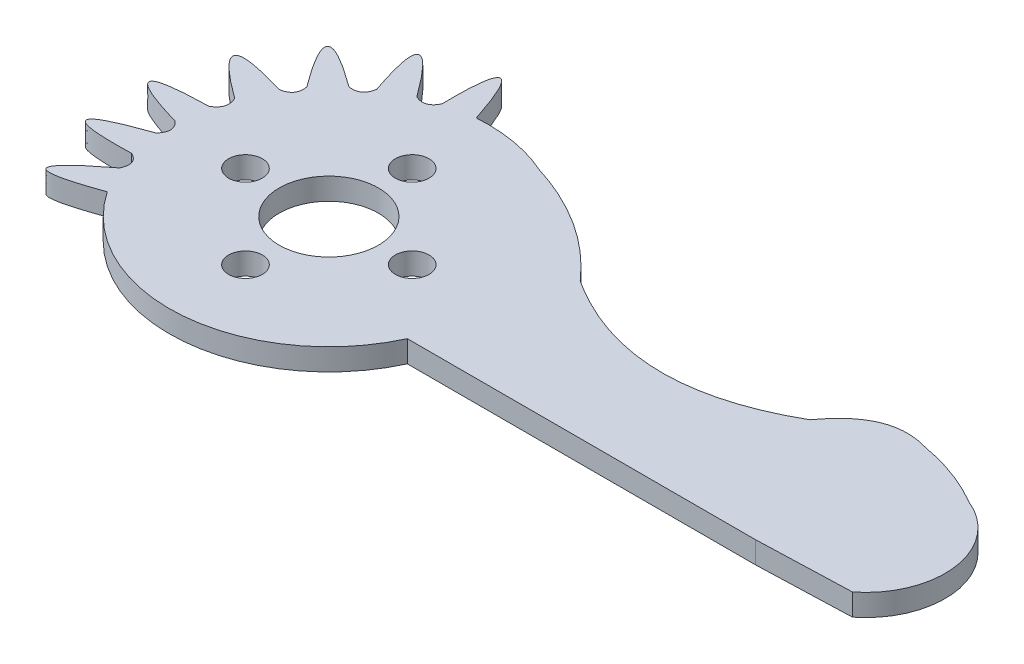
SolidWorks part; units mm, degrees
ref_plane "前视基准面" through (0, 0, 0) normal (0, 0, 1) x (1, 0, 0)
ref_plane "上视基准面" through (0, 0, 0) normal (0, 1, 0) x (1, 0, 0)
ref_plane "右视基准面" through (0, 0, 0) normal (1, 0, 0) x (0, 0, -1)
sketch "草图1" plane through (0, 0, 0) normal (0, 1, 0) x (1, 0, 0)
  line L0 (14.611, -6.7) -> (49.6904, -6.7)
  line L2 (49.6904, -6.7) -> (59.1421, -6.3765)
  arc A0 (6.5551, 14.6766) -> (-1.174, 16.031) centre (0, 0) ccw
  arc A1 (59.1421, -6.3765) -> (57.1955, 7.3271) centre (54.1955, -0.0891) ccw
  arc A4 (-13.3181, -9) -> (14.611, -6.7) centre (0, 0) ccw
  circle A10 centre (0, 0) radius 5
  circle A11 centre (0, 8.4) radius 1.7
  circle A12 centre (8.4, 0) radius 1.7
  circle A13 centre (-8.4, 0) radius 1.7
  circle A14 centre (0, -8.4) radius 1.7
  spline S0 degree 3 poles (50.3471, 9.8802) (52.7614, 9.4439) (55.0442, 8.5928) (57.1955, 7.3271) knots 0.288437 0.288437 0.288437 0.288437 1 1 1 1
  spline S1 degree 2 poles (-14.7879, -6.3) (-14.1793, -5.0235) (-15.4558, -4.4148) knots 0 0 0 1 1 1
  spline S2 degree 2 poles (-13.3181, -9) (-22.836, -12.4311) (-14.7879, -6.3) knots 0 0 0 1 1 1
  spline S3 degree 2 poles (6.5551, 14.6766) (13.509, 12.4928) (18.294, 7.0371) knots 0 0 0 1 1 1
  spline S4 degree 2 poles (-15.4558, -4.4148) (-25.5664, -4.7364) (-16.0116, -1.4148) knots 0 0 0 1 1 1
  spline S5 degree 2 poles (-16.0116, -1.4148) (-15.0379, -0.3941) (-16.0633, 0.5852) knots 0 0 0 1 1 1
  spline S6 degree 2 poles (-16.0633, 0.5852) (-25.7809, 3.3882) (-15.669, 3.5852) knots 0 0 0 1 1 1
  spline S7 degree 2 poles (-15.669, 3.5852) (-14.4125, 4.2993) (-15.0724, 5.5852) knots 0 0 0 1 1 1
  spline S8 degree 2 poles (-15.0724, 5.5852) (-23.2951, 11.5171) (-13.5892, 8.5852) knots 0 0 0 1 1 1
  spline S9 degree 2 poles (-13.5892, 8.5852) (-12.193, 8.8101) (-12.4179, 10.2063) knots 0 0 0 1 1 1
  spline S10 degree 2 poles (-12.4179, 10.2063) (-18.4607, 18.314) (-10.305, 12.3361) knots 0 0 0 1 1 1
  spline S11 degree 2 poles (-10.305, 12.3361) (-8.9071, 12.1223) (-8.6933, 13.5203) knots 0 0 0 1 1 1
  spline S12 degree 2 poles (-8.6933, 13.5203) (-11.9612, 23.0896) (-6.0295, 14.9002) knots 0 0 0 1 1 1
  spline S13 degree 2 poles (-6.0295, 14.9002) (-4.7643, 14.2684) (-4.1325, 15.5337) knots 0 0 0 1 1 1
  spline S14 degree 2 poles (-4.1325, 15.5337) (-4.3112, 25.644) (-1.174, 16.031) knots 0 0 0 1 1 1
  spline S15 degree 3 poles (41.9844, 6.5142) (43.667, 8.849) (46.3171, 10.5568) (49.3037, 10.1961) (50.3471, 9.8802) knots 0.090085 0.090085 0.090085 0.090085 0.520369 0.736119 0.736119 0.736119 0.736119
  spline S16 degree 2 poles (18.294, 7.0371) (29.824, -0.4499) (41.9844, 6.5142) knots 0 0 0 1 1 1
  point P1 (-13.3181, -9)
  point P3 (0, -6.7)
  point P6 (54.1955, -0.0891)
  point P7 (49.6904, -6.7)
  point P8 (51.3181, 4)
  point P9 (57.1955, -0.0891)
  point P12 (54.0636, 4)
  point P13 (-14.7879, -6.3)
  point P15 (32.3181, 6.3)
  point P17 (-18.4445, -10.0406)
  point P24 (-15.4558, -4.4148)
  point P25 (-16.0633, 0.5852)
  point P26 (-16.0116, -1.4148)
  point P27 (-15.669, 3.5852)
  point P28 (-15.0724, 5.5852)
  point P29 (-13.5892, 8.5852)
  point P30 (-12.4179, 10.2063)
  point P31 (-10.305, 12.3361)
  point P32 (-8.6933, 13.5203)
  point P33 (-6.0295, 14.9002)
  point P34 (-4.1325, 15.5337)
  point P35 (-1.174, 16.031)
  point P41 (0, 8.4)
  point P49 (8.4, 0)
  point P51 (-8.4, 0)
  point P52 (0, -8.4)
  point P53 (0, 5)
  point P56 (-5, 0)
  point P58 (0, -5)
  point P60 (5, 0)
  point P61 (0, 6.7)
  point P62 (6.7, 0)
  point P64 (-6.7, 0)
  dimension "D1" = 6.7
  dimension "D6" = 5
  dimension "D2" = 8
  dimension "D3" = 5
  dimension "D4" = 3
  dimension "D5" = 13
  dimension "D7" = 5
  dimension "D8" = 5
  dimension "D9" = 5
  dimension "D10" = 1.7
  dimension "D11" = 1.7
  dimension "D12" = 1.7
  dimension "D13" = 1.7
  dimension "D14" = 1.7
  dimension "D15" = 1.7
  dimension "D16" = 1.7
extrude "凸台-拉伸1" add sketch "草图1" along normal blind 2.2
